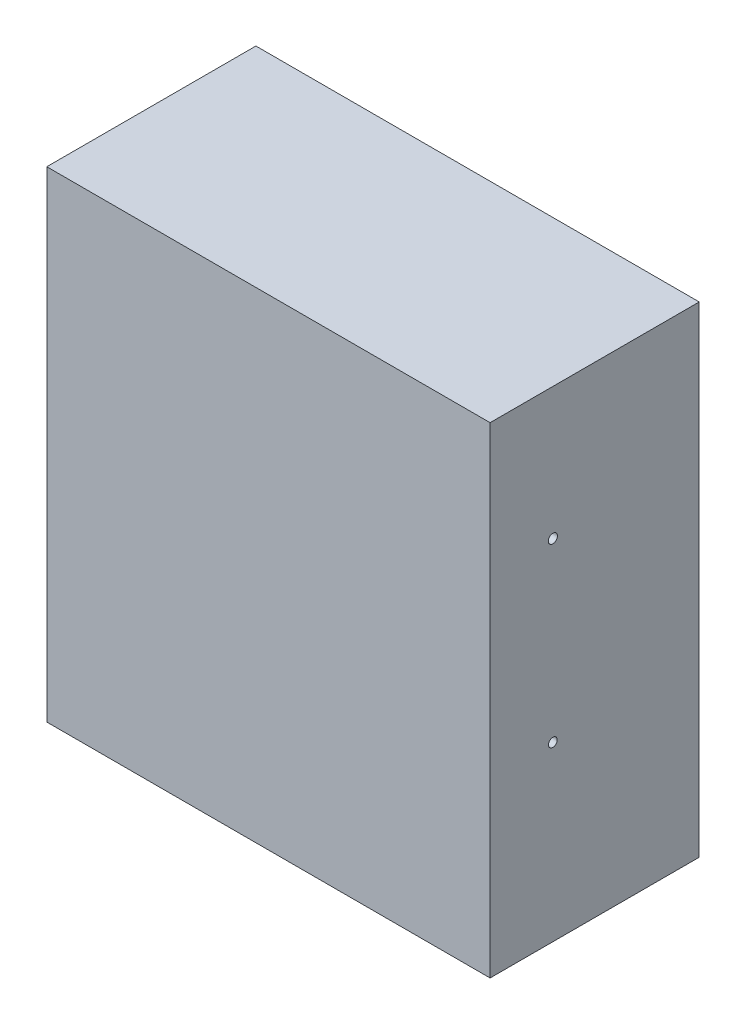
SolidWorks part; units mm, degrees
ref_plane "前基準面" through (0, 0, 0) normal (0, 0, 1) x (1, 0, 0)
ref_plane "上基準面" through (0, 0, 0) normal (0, 1, 0) x (1, 0, 0)
ref_plane "右基準面" through (0, 0, 0) normal (1, 0, 0) x (0, 0, -1)
sketch "草圖1" plane through (0, 0, 0) normal (0, 0, 1) x (1, 0, 0)
  line L1 (-106, 115) -> (106, 115)
  line L2 (-106, 115) -> (-106, -115)
  line L3 (-106, -115) -> (106, -115)
  line L4 (106, 115) -> (106, -115)
  line L5 (0, -115) -> (0, 115) construction
  line L6 (-106, 0) -> (106, 0) construction
  point P0 (0, 0)
  dimension "D1" = 212
  dimension "D2" = 230
extrude "填料-伸長1" add sketch "草圖1" along normal blind 100
sketch "草圖2" plane through (0, -115, 0) normal (0, -1, 0) x (1, 0, 0)
  line L1 (-106, 100) -> (-106, 0) construction
  line L3 (-106, 100) -> (106, 100) construction
  line L4 (-101, 95) -> (101, 95)
  line L5 (-101, 95) -> (-101, 5)
  line L6 (-101, 5) -> (101, 5)
  line L7 (101, 95) -> (101, 5)
  line L8 (0, 5) -> (0, 95) construction
  line L9 (-101, 50) -> (101, 50) construction
  point P6 (0, 50)
  dimension "D1" = 5
  dimension "D2" = 5
extrude "除料-伸長1" cut sketch "草圖2" against normal blind 225
sketch "草圖5" plane through (106, 0, 0) normal (1, 0, 0) x (0, 0, -1)
  circle A0 centre (-69.9889, 52.0092) radius 2.2
extrude "除料-伸長4" cut sketch "草圖5" against normal blind 238
sketch "草圖6" plane through (106, 0, 0) normal (1, 0, 0) x (0, 0, -1)
  line L0 (-69.9889, 49.8092) -> (-69.9889, -32.4)
  circle A0 centre (-69.9889, 52.0092) radius 2.2 construction
  circle A1 centre (-69.9889, -32.4) radius 2.1
extrude "除料-伸長5" cut sketch "草圖6" against normal blind 237
